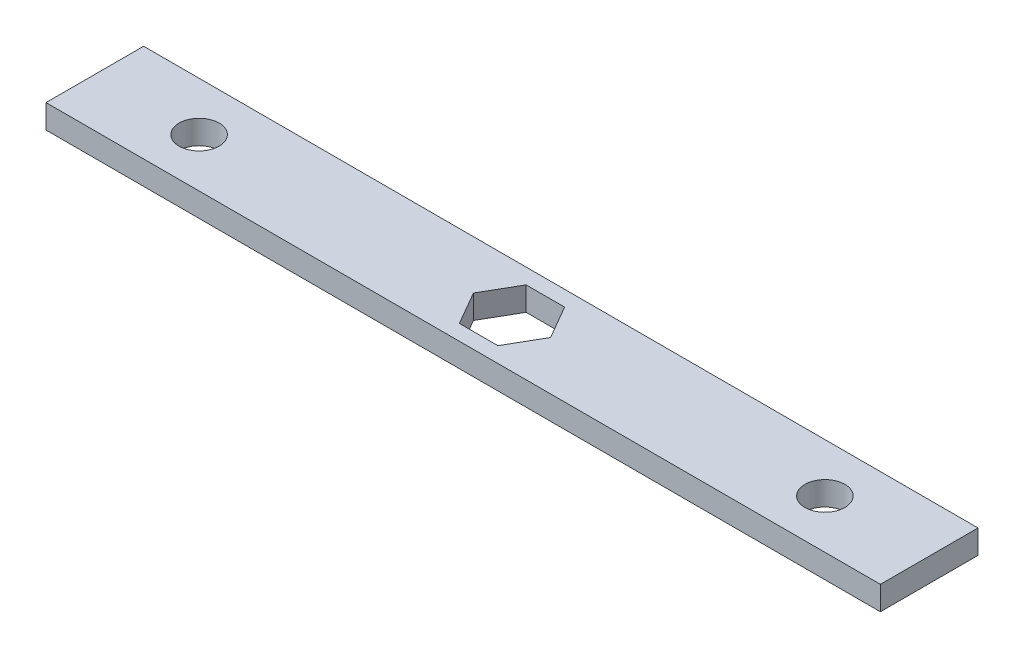
SolidWorks part; units mm, degrees
ref_plane "Front" through (0, 0, 0) normal (0, 0, 1) x (1, 0, 0)
ref_plane "Top" through (0, 0, 0) normal (0, 1, 0) x (1, 0, 0)
ref_plane "Right" through (0, 0, 0) normal (1, 0, 0) x (0, 0, -1)
sketch "Sketch1" plane through (0, 0, 0) normal (0, 1, 0) x (1, 0, 0)
  line L1 (-50, 5.85) -> (50, 5.85)
  line L2 (-50, 5.85) -> (-50, -5.85)
  line L3 (-50, -5.85) -> (50, -5.85)
  line L4 (50, 5.85) -> (50, -5.85)
  line L5 (-50, 5.85) -> (50, -5.85) construction
  line L6 (-50, -5.85) -> (50, 5.85) construction
  point P0 (0, 0)
  dimension "D1" = 11.7
  dimension "D2" = 100
extrude "Boss-Extrude1" add sketch "Sketch1" along normal blind 2.85
sketch "Sketch2" plane through (0, 0, 0) normal (0, -1, 0) x (1, 0, 0)
  line L0 (-2.3094, 4) -> (2.3094, 4)
  line L1 (2.3094, 4) -> (4.6188, 0)
  line L2 (4.6188, 0) -> (2.3094, -4)
  line L3 (2.3094, -4) -> (-2.3094, -4)
  line L4 (-2.3094, -4) -> (-4.6188, 0)
  line L5 (-4.6188, 0) -> (-2.3094, 4)
  circle A0 centre (0, 0) radius 4 construction
  dimension "D1" = 8
extrude "Cut-Extrude1" cut sketch "Sketch2" against normal through all
sketch "Sketch3" plane through (0, 2.85, 0) normal (0, 1, 0) x (1, 0, 0)
  line L0 (-37.5, 0) -> (0, 0) construction
  line L1 (0, 0) -> (37.5, 0) construction
  line L2 (50, -5.85) -> (50, 5.85) construction
  circle A0 centre (-37.5, 0) radius 2.4
  circle A1 centre (37.5, 0) radius 2.4
  dimension "D1" = 4.8
  dimension "D2" = 12.5
extrude "Cut-Extrude2" cut sketch "Sketch3" against normal through all
